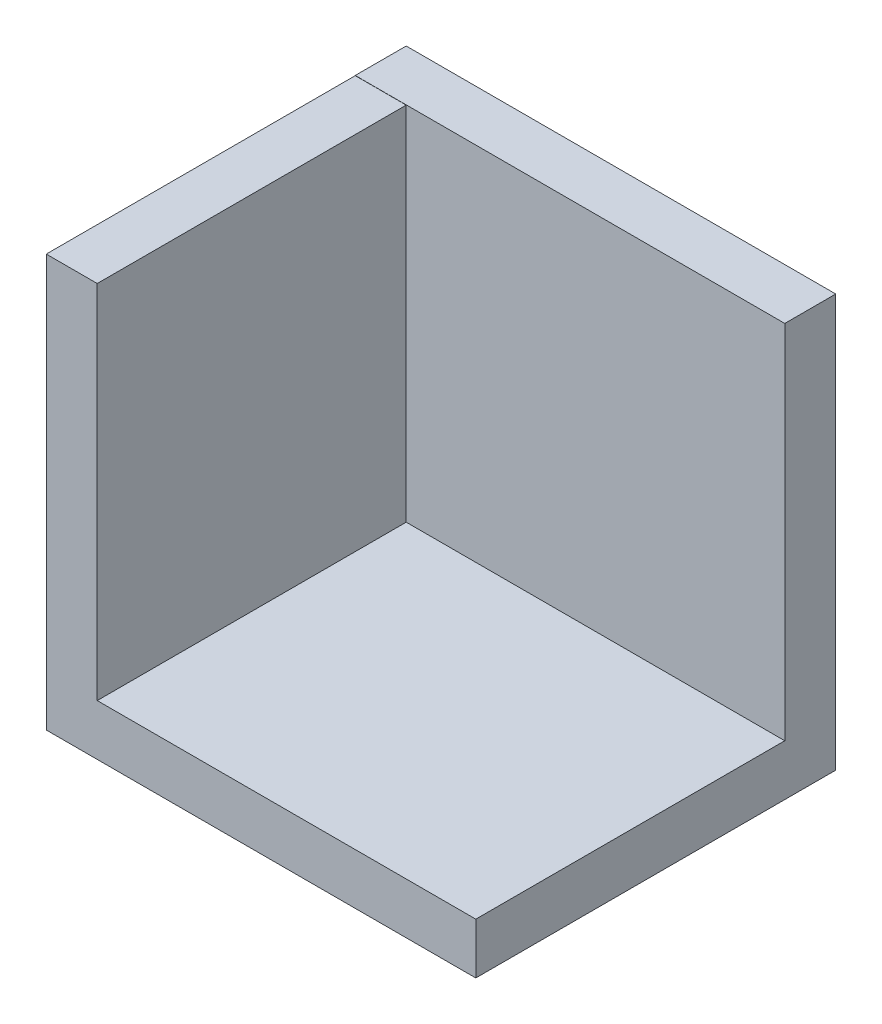
SolidWorks part; units mm, degrees
ref_plane "Front Plane" through (0, 0, 0) normal (0, 0, 1) x (1, 0, 0)
ref_plane "Top Plane" through (0, 0, 0) normal (0, 1, 0) x (1, 0, 0)
ref_plane "Right Plane" through (0, 0, 0) normal (1, 0, 0) x (0, 0, -1)
sketch "Sketch1" plane through (0, 0, 0) normal (1, 0, 0) x (0, 0, -1)
  line L0 (0, 0) -> (67.2624, 0)
  line L1 (67.2624, 0) -> (67.2624, 77.0602)
  line L2 (67.2624, 77.0602) -> (57.7374, 77.0602)
  line L3 (57.7374, 77.0602) -> (57.7374, 9.525)
  line L4 (57.7374, 9.525) -> (0, 9.525)
  line L5 (0, 9.525) -> (0, 0)
extrude "Extrude1" add sketch "Sketch1" against normal blind 80.264
ref_plane "Plane1" through (-80.264, 0, 0) normal (-1, 0, 0) x (0, 0, 1)
sketch "Sketch2" plane through (-80.264, 0, 0) normal (-1, 0, 0) x (0, 0, 1)
  line L2 (-57.7374, 9.525) -> (0, 9.525)
  line L3 (-57.7374, 9.525) -> (-57.7374, 77.0207)
  line L4 (-57.7374, 77.0207) -> (0, 77.0207)
  line L5 (0, 9.525) -> (0, 77.0207)
extrude "Extrude2" add sketch "Sketch2" against normal blind 9.525
